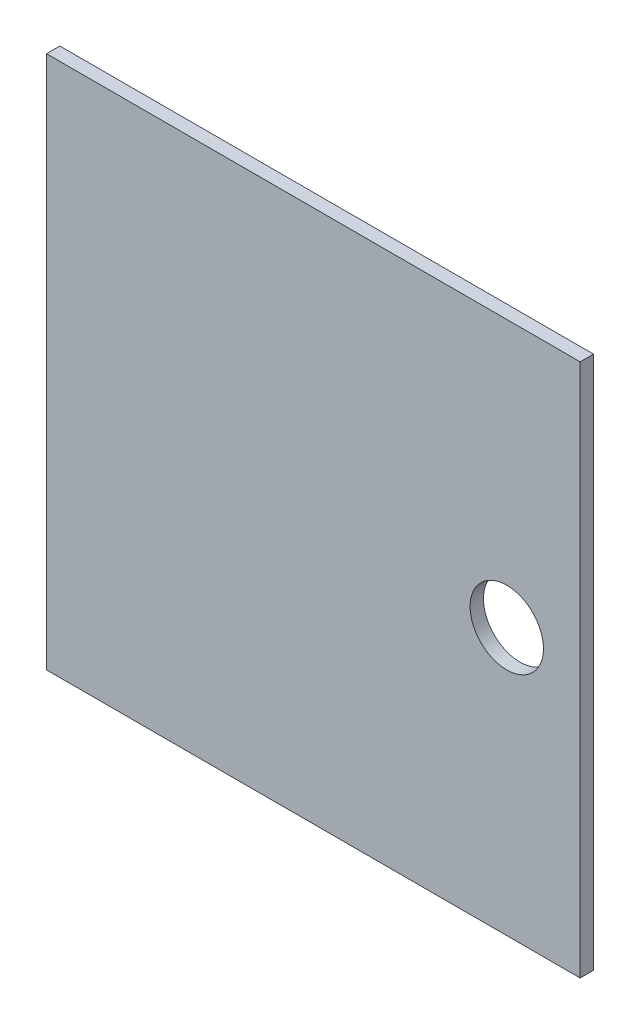
SolidWorks part; units mm, degrees
ref_plane "Front Plane" through (0, 0, 0) normal (0, 0, 1) x (1, 0, 0)
ref_plane "Top Plane" through (0, 0, 0) normal (0, 1, 0) x (1, 0, 0)
ref_plane "Right Plane" through (0, 0, 0) normal (1, 0, 0) x (0, 0, -1)
sketch "Sketch1" plane through (0, 0, 0) normal (0, 0, 1) x (1, 0, 0)
  line L1 (0, 0) -> (400, 0)
  line L2 (0, 0) -> (0, 400)
  line L3 (0, 400) -> (400, 400)
  line L4 (400, 0) -> (400, 400)
  dimension "D1" = 400
  dimension "D2" = 400
extrude "Boss-Extrude1" add sketch "Sketch1" along normal blind 10 contours L3 L4 L1 L2
sketch "Sketch2" plane through (0, 0, 10) normal (0, 0, 1) x (1, 0, 0)
  line L5 (0, 200) -> (50, 200) construction
  line L6 (0, 0) -> (0, 400) construction
  circle A1 centre (55, 200) radius 5
  dimension "D3" = 10
  dimension "D4" = 50
sketch "Sketch4" plane through (0, 0, 10) normal (0, 0, 1) x (1, 0, 0)
  line L0 (400, 200) -> (372.5001, 200) construction
  line L1 (400, 0) -> (400, 400) construction
  line L2 (345.0002, 199.9663) -> (172.0002, 199.9663) construction
  circle A0 centre (345.0002, 199.9663) radius 27.5
  point P7 (400, 200)
  dimension "D2" = 55
  dimension "D3" = 173
  dimension "D1" = 54.9998
extrude "Cut-Extrude1" cut sketch "Sketch4" against normal through all
